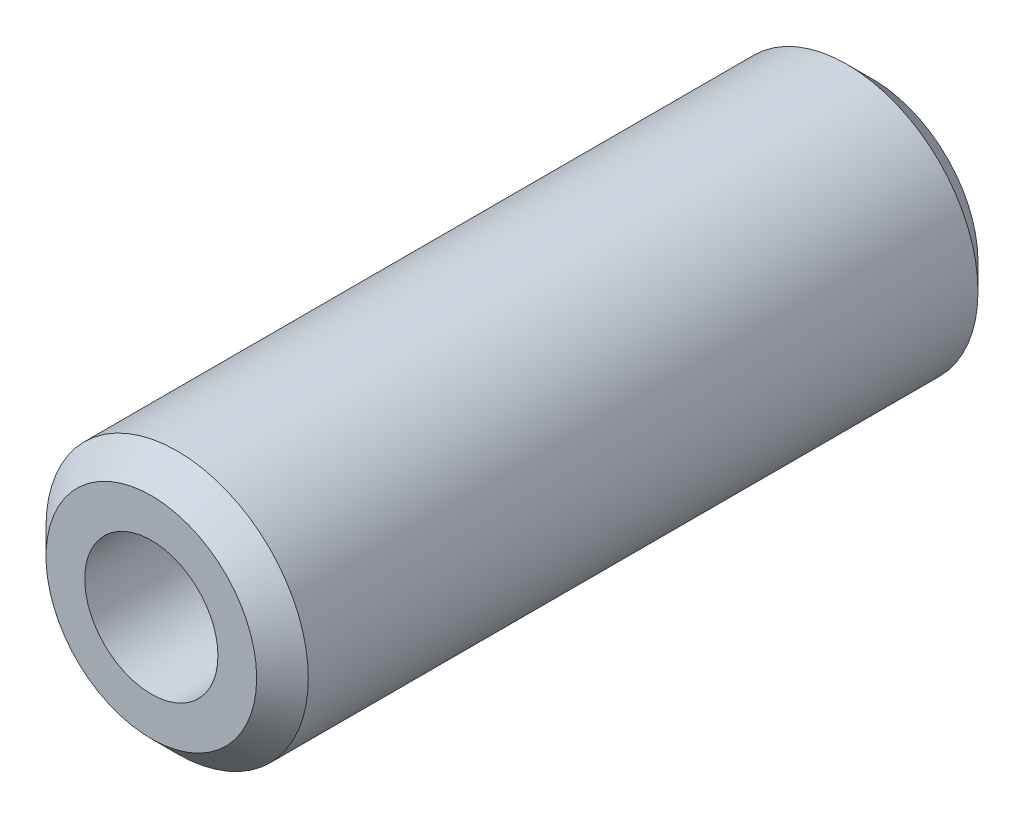
SolidWorks part; units mm, degrees
ref_plane "Front Plane" through (0, 0, 0) normal (0, 0, 1) x (1, 0, 0)
ref_plane "Top Plane" through (0, 0, 0) normal (0, 1, 0) x (1, 0, 0)
ref_plane "Right Plane" through (0, 0, 0) normal (1, 0, 0) x (0, 0, -1)
sketch "Sketch2" plane through (0, 0, 0) normal (0, 0, 1) x (1, 0, 0)
  circle A0 centre (0, 0) radius 12.7
  dimension "D1" = 25.4
extrude "Boss-Extrude1" add sketch "Sketch2" along normal blind 69.85
sketch "Sketch3" plane through (0, 0, 69.85) normal (0, 0, 1) x (1, 0, 0)
  circle A0 centre (0, 0) radius 6.45
  dimension "D1" = 12.9
extrude "Cut-Extrude1" cut sketch "Sketch3" against normal through all
chamfer "Chamfer1" distance 2.5 angle 45 2 edges at (12.7, 0, 0) (12.7, 0, 69.85)
